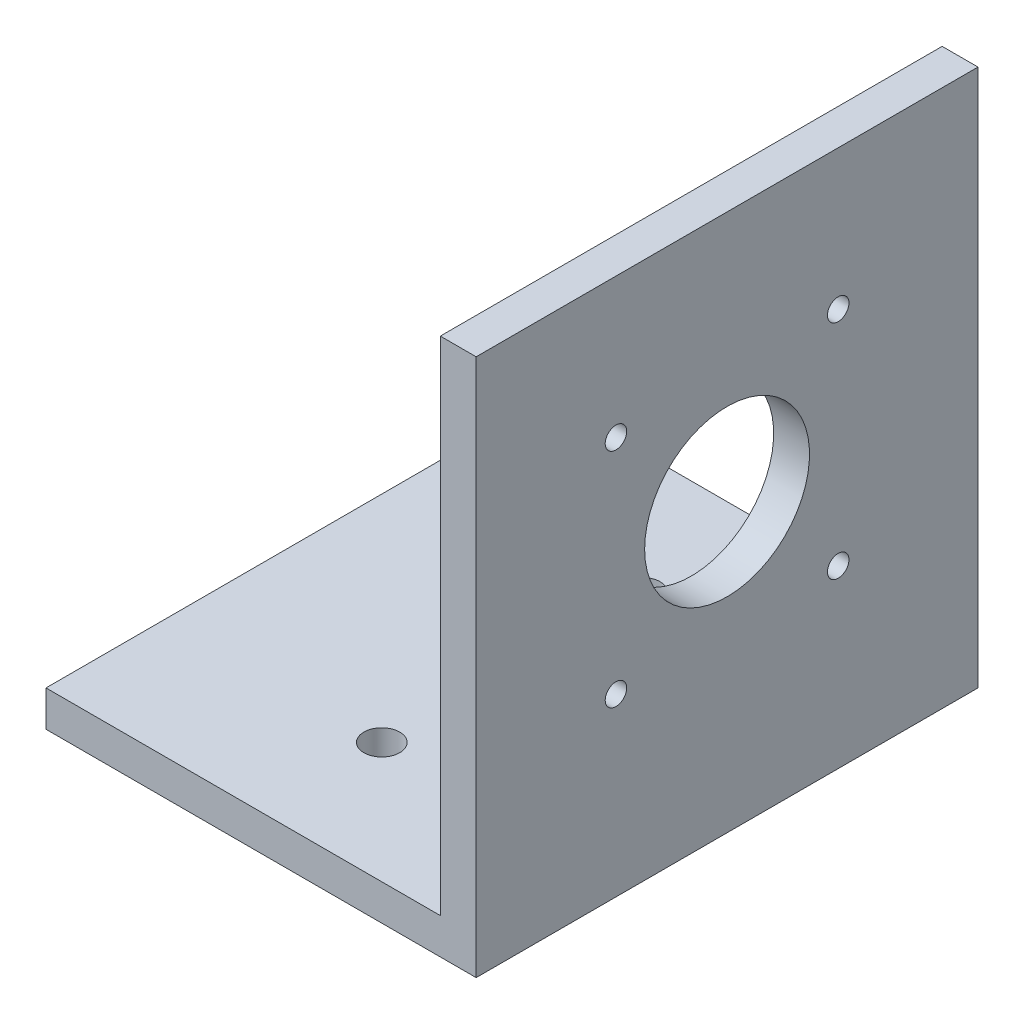
SolidWorks part; units mm, degrees
ref_plane "Front Plane" through (0, 0, 0) normal (0, 0, 1) x (1, 0, 0)
ref_plane "Top Plane" through (0, 0, 0) normal (0, 1, 0) x (1, 0, 0)
ref_plane "Right Plane" through (0, 0, 0) normal (1, 0, 0) x (0, 0, -1)
sketch "Sketch1" plane through (0, 0, 0) normal (0, 1, 0) x (1, 0, 0)
  line L1 (-30, -35) -> (30, -35)
  line L2 (-30, -35) -> (-30, 35)
  line L3 (-30, 35) -> (30, 35)
  line L4 (30, -35) -> (30, 35)
  line L5 (-30, -35) -> (30, 35) construction
  line L6 (-30, 35) -> (30, -35) construction
  point P0 (0, 0)
  dimension "D1" = 70
  dimension "D2" = 60
extrude "Boss-Extrude1" add sketch "Sketch1" along normal blind 5
sketch "Sketch2" plane through (0, 5, 0) normal (0, 1, 0) x (1, 0, 0)
  line L0 (-30, -35) -> (30, -35) construction
  line L1 (30, 35) -> (25, 35)
  line L2 (30, 35) -> (30, -35)
  line L3 (30, -35) -> (25, -35)
  line L4 (25, 35) -> (25, -35)
  dimension "D1" = 5
extrude "Boss-Extrude2" add sketch "Sketch2" along normal blind 70
sketch "Sketch3" plane through (0, 5, 0) normal (0, 1, 0) x (1, 0, 0)
  line L0 (0, 0) -> (-27.4819, 0)
  line L1 (-30, 35) -> (-30, -35) construction
  circle A0 centre (0, 18.1615) radius 2.5
  circle A1 centre (0, -18.1615) radius 2.5
  dimension "D1" = 5
  dimension "D2" = 30
extrude "Cut-Extrude1" cut sketch "Sketch3" against normal blind 70 contours A0 | A1
sketch "Sketch4" plane through (25, 0, 0) normal (-1, 0, 0) x (0, 0, 1)
  line L0 (-35, 75) -> (-35, 5) construction
  line L1 (-35, 75) -> (35, 75) construction
  circle A0 centre (0, 40) radius 11.5
  dimension "D1" = 23
  dimension "D2" = 35
  dimension "D3" = 35
extrude "Cut-Extrude2" cut sketch "Sketch4" against normal blind 10
sketch "Sketch5" plane through (25, 0, 0) normal (-1, 0, 0) x (0, 0, 1)
  line L1 (-15.5, 24.5) -> (15.5, 24.5)
  line L2 (-15.5, 24.5) -> (-15.5, 55.5)
  line L3 (-15.5, 55.5) -> (15.5, 55.5)
  line L4 (15.5, 24.5) -> (15.5, 55.5)
  line L5 (-15.5, 24.5) -> (15.5, 55.5) construction
  line L6 (-15.5, 55.5) -> (15.5, 24.5) construction
  circle A0 centre (-15.5, 55.5) radius 1.5
  circle A1 centre (15.5, 55.5) radius 1.5
  circle A2 centre (15.5, 24.5) radius 1.5
  circle A3 centre (-15.5, 24.5) radius 1.5
  point P0 (0, 40)
  dimension "D3" = 3
  dimension "D1" = 31
  dimension "D2" = 31
extrude "Cut-Extrude3" cut sketch "Sketch5" against normal blind 10 contours A0 | A1 | A2 | A3
